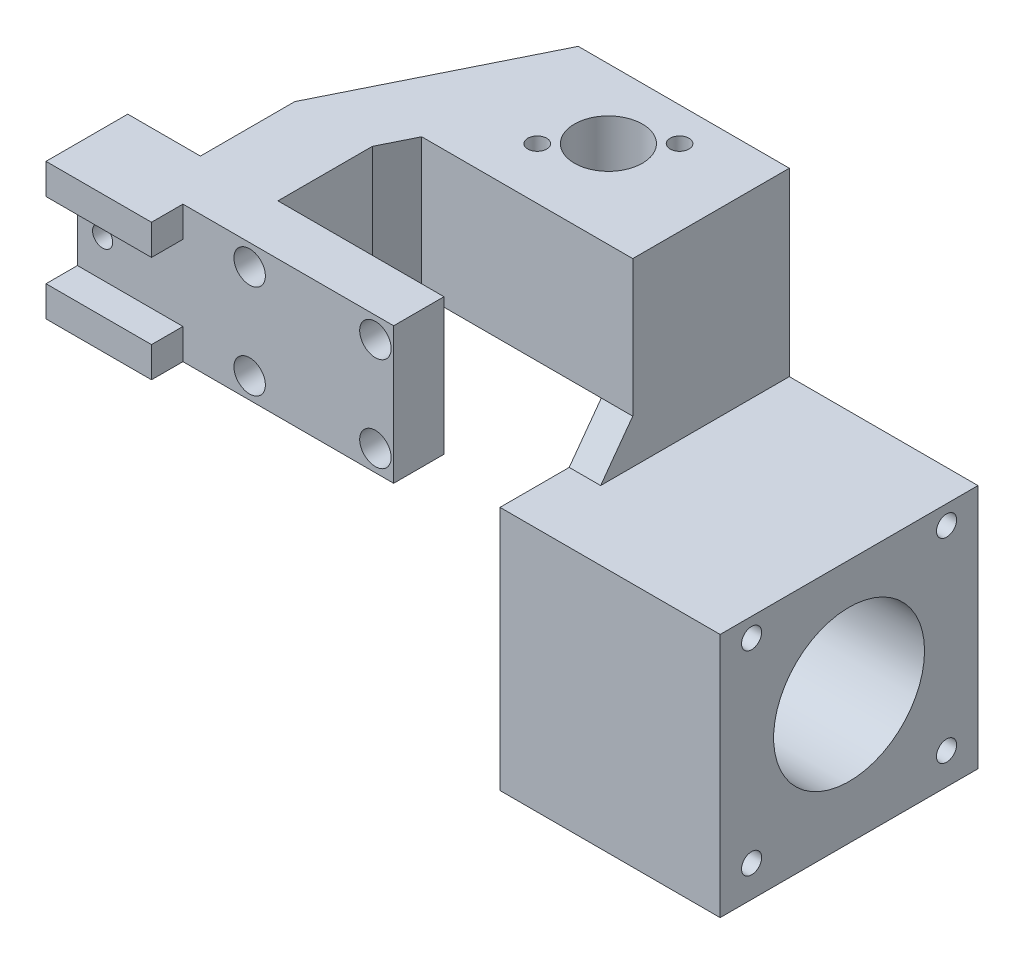
SolidWorks part; units mm, degrees
ref_plane "Přední rovina" through (0, 0, 0) normal (0, 0, 1) x (1, 0, 0)
ref_plane "Horní rovina" through (0, 0, 0) normal (0, 1, 0) x (1, 0, 0)
ref_plane "Pravá rovina" through (0, 0, 0) normal (1, 0, 0) x (0, 0, -1)
sketch "Skica1" plane through (0, 0, 0) normal (0, 0, 1) x (1, 0, 0)
  line L1 (16.212, -19.9414) -> (-34.0669, -19.9414)
  line L2 (16.212, -19.9414) -> (16.212, 1.7586)
  line L3 (16.212, 1.7586) -> (-34.0669, 1.7586)
  line L4 (-34.0669, -19.9414) -> (-34.0669, 1.7586)
  circle A0 centre (13.312, -16.5914) radius 1.6
  circle A1 centre (-6.688, -16.5914) radius 1.6
  circle A2 centre (-6.688, -1.5914) radius 1.6
  circle A3 centre (13.312, -1.5914) radius 1.6
  dimension "D1" = 3.2
  dimension "D2" = 2
  dimension "D3" = 2
extrude "Přidat vysunutím1" add sketch "Skica1" along normal blind 8
sketch "Skica2" plane through (0, 0, 8) normal (0, 0, 1) x (1, 0, 0)
  circle A0 centre (13.312, -16.5914) radius 2.5
  circle A1 centre (-6.688, -16.5914) radius 2.5
  circle A2 centre (-6.688, -1.5914) radius 2.5
  circle A3 centre (13.312, -1.5914) radius 2.5
  dimension "D1" = 5
  dimension "D2" = 2
  dimension "D3" = 2
extrude "Odebrat vysunutím1" cut sketch "Skica2" against normal blind 4
sketch "Skica3" plane through (0, 0, 8) normal (0, 0, 1) x (1, 0, 0)
  line L0 (-34.0669, 1.7586) -> (-34.0669, -19.9414) construction
  circle A0 centre (-30.0669, -9.0914) radius 1.6
  dimension "D1" = 3.2
  dimension "D2" = 4
extrude "Odebrat vysunutím2" cut sketch "Skica3" against normal blind 8
sketch "Skica4" plane through (0, 0, 0) normal (0, 0, -1) x (-1, 0, 0)
  line L0 (-16.212, 1.7586) -> (34.0669, 1.7586) construction
  line L1 (10.188, 1.7586) -> (22.5157, 1.7586)
  line L2 (10.188, 1.7586) -> (10.188, -19.9414)
  line L3 (10.188, -19.9414) -> (22.5157, -19.9414)
  line L4 (22.5157, 1.7586) -> (22.5157, -19.9414)
  line L5 (10.188, 1.7586) -> (10.188, -19.9414) construction
  line L6 (34.0669, -19.9414) -> (-16.212, -19.9414) construction
  line L7 (10.188, -19.9414) -> (10.188, 1.7586) construction
extrude "Přidat vysunutím2" add sketch "Skica4" along normal blind 15
sketch "Skica6" plane through (0, 1.7586, 0) normal (0, 1, 0) x (1, 0, 0)
  line L0 (-10.188, 15) -> (-22.5157, 15)
  line L1 (-10.188, 15) -> (-7.5858, 20.255)
  line L2 (-22.5157, 15) -> (-7.5858, 45.15)
  line L3 (4.7419, 45.15) -> (-7.5858, 45.15)
  line L5 (-7.5858, 45.15) -> (20.9737, 45.15)
  line L7 (-7.5858, 20.255) -> (20.9737, 20.255)
  line L8 (20.9737, 45.15) -> (20.9737, 20.255)
  circle A0 centre (8.2082, 34.15) radius 11 construction
  circle A3 centre (8.2082, 34.15) radius 5.4063
  line M11 (-10.188, 15) -> (-22.5157, 15)
extrude "Přidat vysunutím3" add sketch "Skica6" against normal up to surface (21.7 mm away) contours L8 L5 L3 L2 L1 L7 A3 M11 up to face at (-12.6397, -19.9414, -1.75)
sketch "Skica7" plane through (0, -19.9414, 0) normal (0, -1, 0) x (1, 0, 0)
  line L0 (8.2082, -34.15) -> (0.2082, -34.15) construction
  line L1 (8.2082, -34.15) -> (2.5514, -28.4931) construction
  line L2 (8.2082, -34.15) -> (13.8651, -39.8069) construction
  circle A0 centre (8.2082, -34.15) radius 8 construction
  circle A1 centre (2.5514, -28.4931) radius 1.5
  circle A2 centre (13.8651, -39.8069) radius 1.5
  point P12 (8.2082, -34.15)
  dimension "D1" = 16
  dimension "D2" = 3
  dimension "D3" = 2
extrude "Odebrat vysunutím3" cut sketch "Skica7" against normal up to surface (21.7 mm away) up to face at (-6.1951, 1.7586, -12.0675)
sketch "Skica9" plane through (20.9737, 0, 0) normal (1, 0, 0) x (0, 0, -1)
  line L0 (20.255, -19.9414) -> (15, -19.9414) construction
  line L1 (40.15, -29.9414) -> (9.15, -29.9414) construction
  line L2 (40.15, -29.9414) -> (40.15, -60.9414) construction
  line L3 (40.15, -60.9414) -> (9.15, -60.9414) construction
  line L4 (9.15, -29.9414) -> (9.15, -60.9414) construction
  line L5 (45.15, 1.7586) -> (20.255, 1.7586)
  line L6 (45.15, 1.7586) -> (45.15, -19.9414)
  line L8 (20.255, 1.7586) -> (20.255, -19.9414)
  line L10 (45.15, -19.9414) -> (45.15, -65.9414)
  line L11 (45.15, -65.9414) -> (15.15, -65.9414)
  line L13 (15.15, -60.9414) -> (15.15, -65.9414)
  line L14 (15.15, -65.9414) -> (4.15, -65.9414)
  line L15 (15.15, -65.9414) -> (15.15, -60.9414)
  line L16 (15.15, -26.9414) -> (4.15, -26.9414)
  line L17 (4.15, -65.9414) -> (4.15, -26.9414)
  line L19 (15.15, -26.9414) -> (20.255, -19.9414)
  line L20 (24.65, -45.4414) -> (9.15, -45.4414) construction
  line L21 (24.65, -45.4414) -> (24.65, -60.9414) construction
  circle A0 centre (40.15, -60.9414) radius 1.6
  circle A1 centre (9.15, -60.9414) radius 1.6
  circle A2 centre (9.15, -29.9414) radius 1.6
  circle A3 centre (40.15, -29.9414) radius 1.6
  circle A4 centre (24.65, -45.4414) radius 12
  dimension "D2" = 3.2
  dimension "D8" = 24
  dimension "D1" = 31
  dimension "D5" = 10
  dimension "D6" = 5
  dimension "D7" = 5
  dimension "D9" = 5
  dimension "D10" = 3
  dimension "D3" = 2
  dimension "D4" = 2
extrude "Přidat vysunutím4" add sketch "Skica9" along normal blind 5
sketch "Skica10" plane through (25.9737, 0, 0) normal (1, 0, 0) x (0, 0, -1)
  line L1 (4.15, -26.9414) -> (45.15, -26.9414)
  line L2 (4.15, -26.9414) -> (4.15, -65.9414)
  line L3 (4.15, -65.9414) -> (45.15, -65.9414)
  line L4 (45.15, -26.9414) -> (45.15, -65.9414)
  circle A0 centre (24.65, -45.4414) radius 12 construction
  circle A1 centre (40.15, -60.9414) radius 1.6 construction
  circle A2 centre (40.15, -29.9414) radius 1.6 construction
  circle A3 centre (9.15, -29.9414) radius 1.6 construction
  circle A4 centre (9.15, -60.9414) radius 1.6 construction
  circle A5 centre (24.65, -45.4414) radius 12
  circle A6 centre (40.15, -60.9414) radius 1.6
  circle A7 centre (40.15, -29.9414) radius 1.6
  circle A8 centre (9.15, -29.9414) radius 1.6
  circle A9 centre (9.15, -60.9414) radius 1.6
extrude "Přidat vysunutím5" add sketch "Skica10" along normal blind 30
sketch "Skica11" plane through (0, 0, 8) normal (0, 0, 1) x (1, 0, 0)
  line L0 (-34.0669, -19.9414) -> (16.212, -19.9414) construction
  line L1 (-34.0669, -15.0914) -> (-17.293, -15.0914)
  line L3 (-34.0669, -3.0914) -> (-17.293, -3.0914)
  line L7 (-34.0669, 1.7586) -> (-17.293, 1.7586)
  line L8 (-34.0669, 1.7586) -> (-34.0669, -3.0914)
  line L9 (-34.0669, -19.9414) -> (-17.293, -19.9414)
  line L10 (-17.293, 1.7586) -> (-17.293, -3.0914)
  line L11 (-17.293, -15.0914) -> (-17.293, -19.9414)
  line L13 (-34.0669, -15.0914) -> (-34.0669, -19.9414)
  point P0 (-30.0669, -9.0914)
  dimension "D1" = 12
extrude "Přidat vysunutím6" add sketch "Skica11" along normal blind 5
